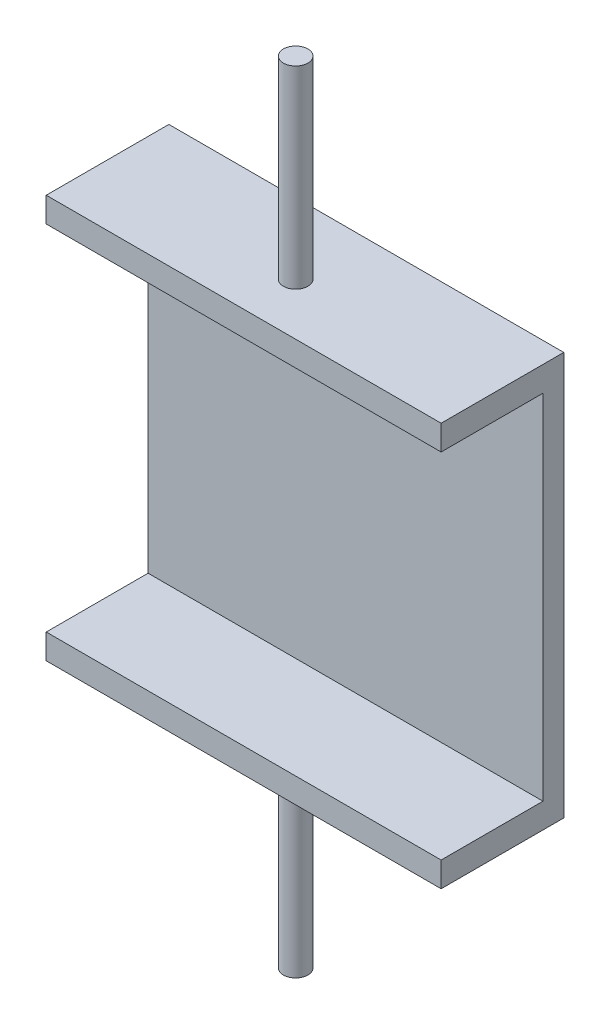
SolidWorks part; units mm, degrees
ref_plane "Front Plane" through (0, 0, 0) normal (0, 0, 1) x (1, 0, 0)
ref_plane "Top Plane" through (0, 0, 0) normal (0, 1, 0) x (1, 0, 0)
ref_plane "Right Plane" through (0, 0, 0) normal (1, 0, 0) x (0, 0, -1)
ref_plane "Plane1" through (0, 0, 123) normal (0, 0, 1) x (1, 0, 0)
sketch "Sketch1" plane through (0, 0, 123) normal (0, 0, 1) x (1, 0, 0)
  line L1 (205, 215) -> (395, 215)
  line L2 (205, 215) -> (205, 385)
  line L3 (205, 385) -> (395, 385)
  line L4 (395, 215) -> (395, 385)
extrude "Boss-Extrude1" add sketch "Sketch1" along normal blind 10
ref_plane "Plane2" through (0, 385, 0) normal (0, 1, 0) x (1, 0, 0)
sketch "Sketch2" plane through (0, 385, 0) normal (0, 1, 0) x (1, 0, 0)
  line L0 (-93.5, -123) -> (93.5, -123) construction
  line L1 (205, -123) -> (395, -123)
  line L2 (205, -123) -> (205, -182)
  line L3 (205, -182) -> (395, -182)
  line L4 (395, -123) -> (395, -182)
extrude "Boss-Extrude2" add sketch "Sketch2" along normal blind 12
ref_plane "Plane3" through (0, 203, 0) normal (0, 1, 0) x (1, 0, 0)
sketch "Sketch3" plane through (0, 203, 0) normal (0, 1, 0) x (1, 0, 0)
  line L0 (-100.1, -123) -> (100.1, -123) construction
  line L1 (205, -123) -> (395, -123)
  line L2 (205, -123) -> (205, -182)
  line L3 (205, -182) -> (395, -182)
  line L4 (395, -123) -> (395, -182)
extrude "Boss-Extrude3" add sketch "Sketch3" along normal blind 12
ref_plane "Plane4" through (0, 385, 0) normal (0, 1, 0) x (1, 0, 0)
sketch "Sketch4" plane through (0, 385, 0) normal (0, 1, 0) x (1, 0, 0)
  circle A0 centre (300, -157) radius 5.9
extrude "Boss-Extrude4" add sketch "Sketch4" along normal blind 105
ref_plane "Plane5" through (0, 110, 0) normal (0, 1, 0) x (1, 0, 0)
sketch "Sketch5" plane through (0, 110, 0) normal (0, 1, 0) x (1, 0, 0)
  circle A0 centre (300, -157) radius 5.9
extrude "Boss-Extrude5" add sketch "Sketch5" along normal blind 105
